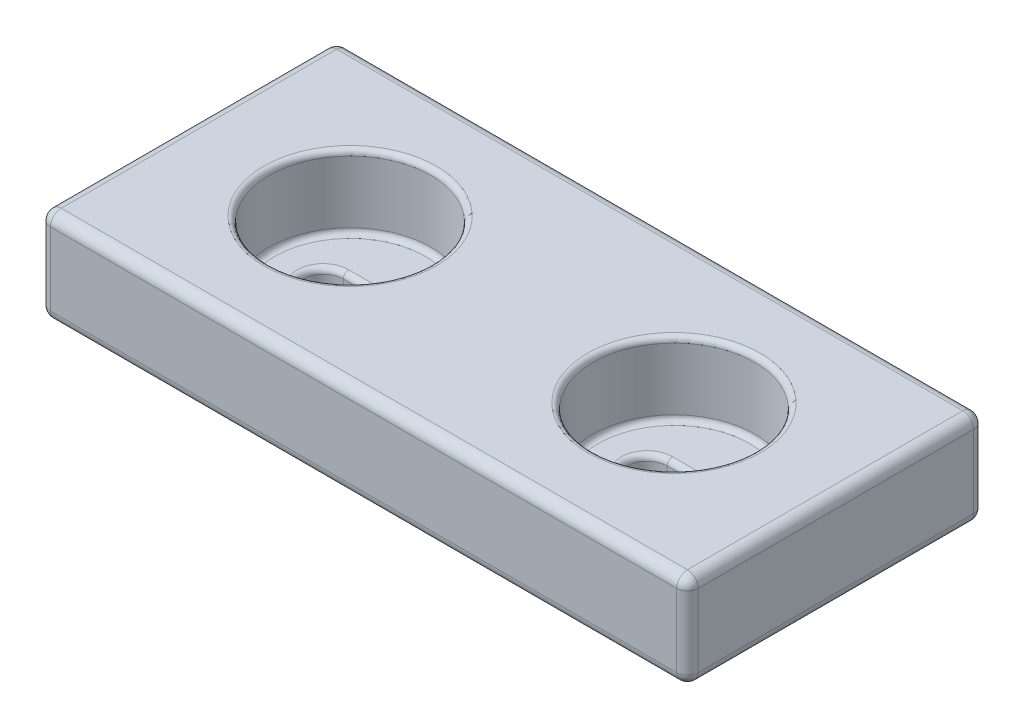
SolidWorks part; units mm, degrees
ref_plane "Front Plane" through (0, 0, 0) normal (0, 0, 1) x (1, 0, 0)
ref_plane "Top Plane" through (0, 0, 0) normal (0, 1, 0) x (1, 0, 0)
ref_plane "Right Plane" through (0, 0, 0) normal (1, 0, 0) x (0, 0, -1)
sketch "Sketch1" plane through (0, 0, 0) normal (0, 1, 0) x (1, 0, 0)
  line L1 (-76.2, 34.925) -> (76.2, 34.925)
  line L2 (-76.2, 34.925) -> (-76.2, -34.925)
  line L3 (-76.2, -34.925) -> (76.2, -34.925)
  line L4 (76.2, 34.925) -> (76.2, -34.925)
  point P4 (0, 34.925)
  point P6 (-76.2, 0)
  dimension "D1" = 152.4
  dimension "D2" = 69.85
extrude "Boss-Extrude1" add sketch "Sketch1" along normal blind 22.225
fillet "Fillet1" radius 2.54 12 edges at (76.2, 11.1125, -34.925) (-76.2, 11.1125, -34.925) (-76.2, 11.1125, 34.925) (76.2, 11.1125, 34.925) (0, 0, 34.925) (76.2, 0, 0) (0, 0, -34.925) (-76.2, 0, 0) (0, 22.225, -34.925) (76.2, 22.225, 0) (0, 22.225, 34.925) (-76.2, 22.225, 0)
sketch "Sketch3" plane through (0, 22.225, 0) normal (0, 1, 0) x (1, 0, 0)
  circle A0 centre (-38.1, 0) radius 19.05
  circle A1 centre (38.1, 0) radius 19.05
  point P4 (0, 0)
  dimension "D1" = 38.1
  dimension "D2" = 38.1
  dimension "D3" = 38.1
  dimension "D4" = 38.1
extrude "Cut-Extrude1" cut sketch "Sketch3" against normal offset from surface (17.145 mm away) 5.08 up to face at (0, 0, 0)
sketch "Sketch4" plane through (0, 22.225, 0) normal (0, 1, 0) x (1, 0, 0)
  line L0 (-31.75, 0) -> (-44.45, 0) construction
  line L1 (-31.75, -4.7625) -> (-44.45, -4.7625)
  line L2 (-31.75, 4.7625) -> (-44.45, 4.7625)
  line L3 (44.45, 0) -> (31.75, 0) construction
  line L4 (44.45, -4.7625) -> (31.75, -4.7625)
  line L5 (44.45, 4.7625) -> (31.75, 4.7625)
  arc A0 (-31.75, -4.7625) -> (-31.75, 4.7625) centre (-31.75, 0) ccw
  arc A1 (-44.45, 4.7625) -> (-44.45, -4.7625) centre (-44.45, 0) ccw
  arc A2 (44.45, -4.7625) -> (44.45, 4.7625) centre (44.45, 0) ccw
  arc A3 (31.75, 4.7625) -> (31.75, -4.7625) centre (31.75, 0) ccw
  point P2 (-38.1, 0)
  point P11 (38.1, 0)
  dimension "D1" = 12.7
  dimension "D2" = 9.525
  dimension "D3" = 12.7
  dimension "D4" = 9.525
extrude "Cut-Extrude2" cut sketch "Sketch4" against normal through all
fillet "Fillet2" radius 1.27 20 edges at (-38.1, 0, -4.7625) (-26.9875, 0, 0) (-38.1, 0, 4.7625) (-38.1, 5.08, -4.7625) (-26.9875, 5.08, 0) (-38.1, 5.08, 4.7625) (-49.2125, 0, 0) (-49.2125, 5.08, 0) (38.1, 0, -4.7625) (49.2125, 0, 0) (38.1, 0, 4.7625) (38.1, 5.08, -4.7625) (49.2125, 5.08, 0) (38.1, 5.08, 4.7625) (26.9875, 0, 0) (26.9875, 5.08, 0) (38.1, 22.225, 19.05) (38.1, 5.08, 19.05) (-38.1, 22.225, 19.05) (-38.1, 5.08, 19.05)
